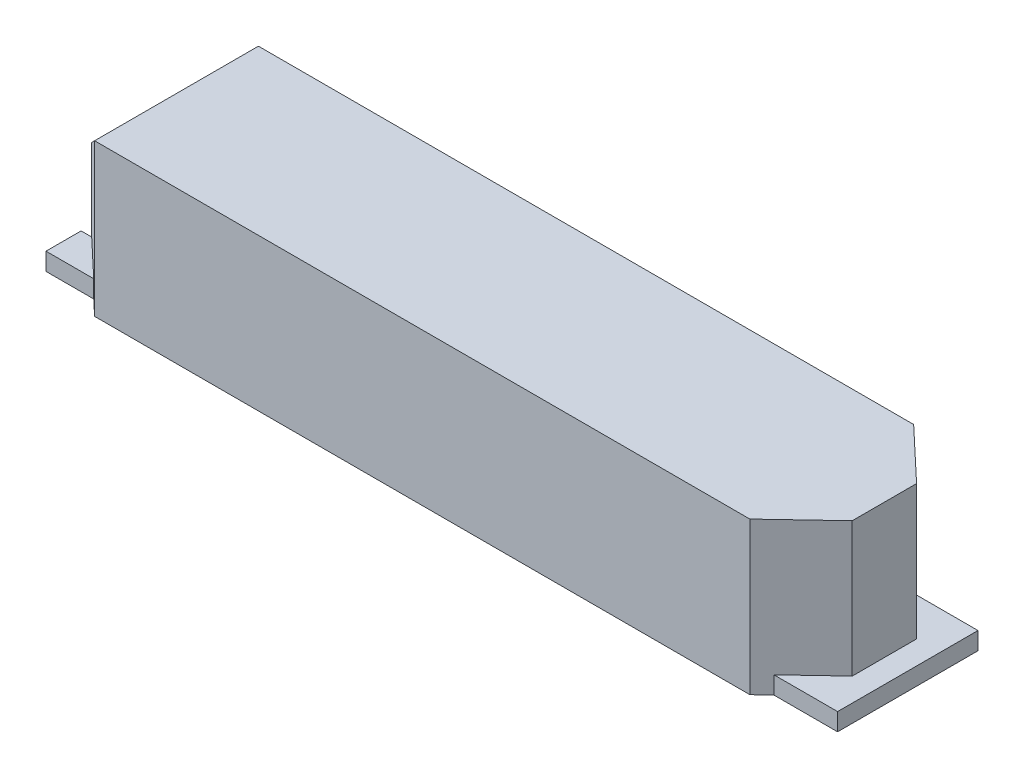
SolidWorks part; units mm, degrees
ref_plane "Front Plane" through (0, 0, 0) normal (0, 0, 1) x (1, 0, 0)
ref_plane "Top Plane" through (0, 0, 0) normal (0, 1, 0) x (1, 0, 0)
ref_plane "Right Plane" through (0, 0, 0) normal (1, 0, 0) x (0, 0, -1)
sketch "Sketch1" plane through (0, 0, 0) normal (0, 1, 0) x (1, 0, 0)
  line L0 (-4.0372, 0) -> (4.5367, 0) construction
  line L1 (0, -1.5101) -> (0, 1.9129) construction
  line L2 (2.8, -0.7) -> (-2.8, -0.7)
  line L3 (-3.25, 0.275) -> (-3.25, -0.275)
  line L4 (-3.25, -0.275) -> (-2.8, -0.7)
  line L5 (3.25, 0.275) -> (3.25, -0.275)
  line L6 (3.25, -0.275) -> (2.8, -0.7)
  line L7 (3.25, 0.275) -> (2.8, 0.7)
  line L8 (2.8, 0.7) -> (-2.8, 0.7)
  line L9 (-3.25, 0.275) -> (-2.8, 0.7)
  point P12 (0, -0.7)
  point P13 (3.25, 0)
  point P16 (-3.25, 0)
  dimension "D1" = 0.7
  dimension "D2" = 2.8
  dimension "D3" = 3.25
  dimension "D4" = 0.275
extrude "Boss-Extrude1" add sketch "Sketch1" along normal blind 1.3
sketch "Sketch2" plane through (0, 0, 0.7) normal (0, 0, 1) x (1, 0, 0)
  line L0 (-2.8, 1.3) -> (-3.25, 0.85)
  line L1 (-3.25, 0.85) -> (-3.4872, 1.3388)
  line L2 (-3.4872, 1.3388) -> (-2.8, 1.3)
  line L3 (-2.8, 1.3) -> (2.8, 1.3) construction
  line L4 (-3.25, 1.3) -> (-3.25, 0) construction
  dimension "D1" = 0.45
extrude "Cut-Extrude1" cut sketch "Sketch2" against normal through all
sketch "Sketch4" plane through (0, 0, 0) normal (0, -1, 0) x (1, 0, 0)
  line L0 (-3.4112, 0) -> (4.0883, 0) construction
  line L1 (3.45, -0.6) -> (3.45, 0.6)
  line L2 (3.45, 0.6) -> (2.85, 0.6)
  line L3 (2.85, 0.6) -> (2.85, -0.6)
  line L4 (3.45, -0.6) -> (2.85, -0.6)
  line L5 (-3.3403, 0.275) -> (-3.3403, 0.575)
  line L6 (-3.3403, 0.575) -> (-2.7903, 0.575)
  line L7 (-3.3403, 0.275) -> (-2.7903, 0.275)
  line L8 (-2.7903, 0.275) -> (-2.7903, 0.575)
  line L9 (-3.3403, -0.275) -> (-3.3403, -0.575)
  line L10 (-3.3403, -0.275) -> (-2.7903, -0.275)
  line L11 (-2.7903, -0.275) -> (-2.7903, -0.575)
  line L12 (-3.3403, -0.575) -> (-2.7903, -0.575)
  point P8 (2.85, 0)
  point P9 (3.45, 0)
  dimension "D1" = 3.45
  dimension "D2" = 0.6
  dimension "D3" = 0.6
  dimension "D4" = 0.3
  dimension "D5" = 0.275
  dimension "D6" = 0.55
extrude "Boss-Extrude2" add sketch "Sketch4" against normal blind 0.15
